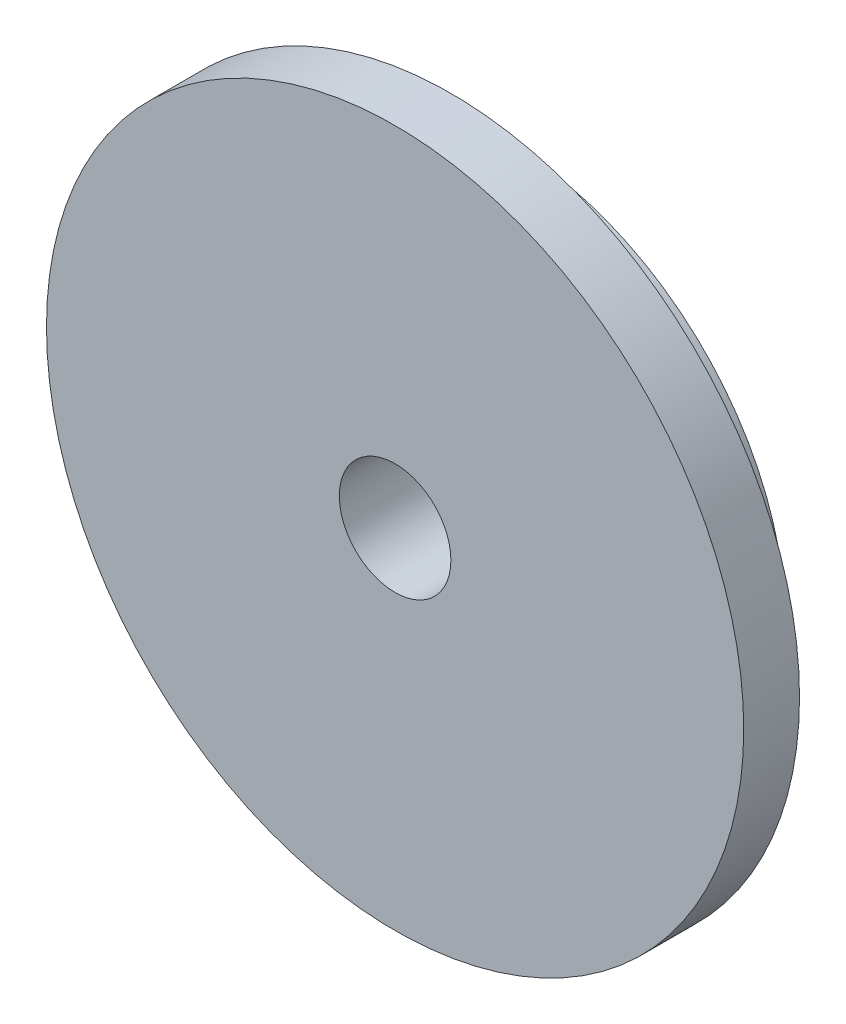
SolidWorks part; units mm, degrees
material "PLA"
ref_plane "Front Plane" through (0, 0, 0) normal (0, 0, 1) x (1, 0, 0)
ref_plane "Top Plane" through (0, 0, 0) normal (0, 1, 0) x (1, 0, 0)
ref_plane "Right Plane" through (0, 0, 0) normal (1, 0, 0) x (0, 0, -1)
sketch "Sketch1" plane through (0, 0, 0) normal (0, 0, 1) x (1, 0, 0)
  circle A0 centre (0, 0) radius 10
  circle A1 centre (0, 0) radius 2
  dimension "D1" = 20
  dimension "D2" = 4
extrude "Boss-Extrude1" add sketch "Sketch1" along normal blind 4
sketch "Sketch2" plane through (0, 0, 4) normal (0, 0, 1) x (1, 0, 0)
  circle A0 centre (0, 0) radius 10
  circle A1 centre (0, 0) radius 12.5
  dimension "D1" = 20
  dimension "D2" = 25
extrude "Boss-Extrude2" add sketch "Sketch2" against normal blind 2
